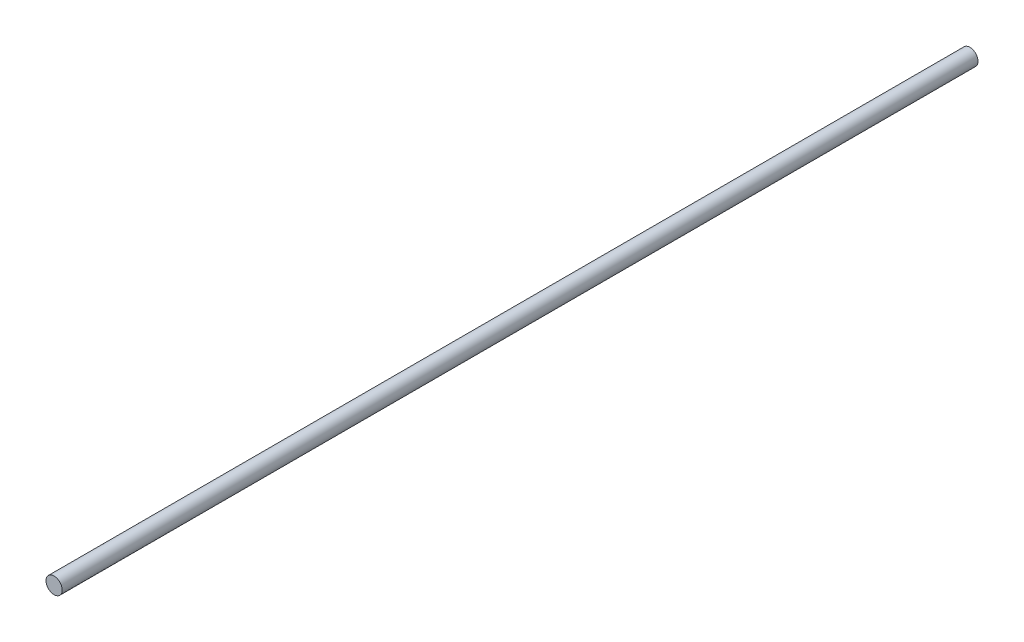
SolidWorks part; units mm, degrees
material "Простая углеродистая сталь"
ref_plane "Спереди" through (0, 0, 0) normal (0, 0, 1) x (1, 0, 0)
ref_plane "Сверху" through (0, 0, 0) normal (0, 1, 0) x (1, 0, 0)
ref_plane "Справа" through (0, 0, 0) normal (1, 0, 0) x (0, 0, -1)
sketch "Эскиз1" plane through (0, 0, 0) normal (0, 0, 1) x (1, 0, 0)
  circle A0 centre (0, 0) radius 5
  dimension "D1" = 10
extrude "Бобышка-Вытянуть1" add sketch "Эскиз1" along normal mid plane 565
